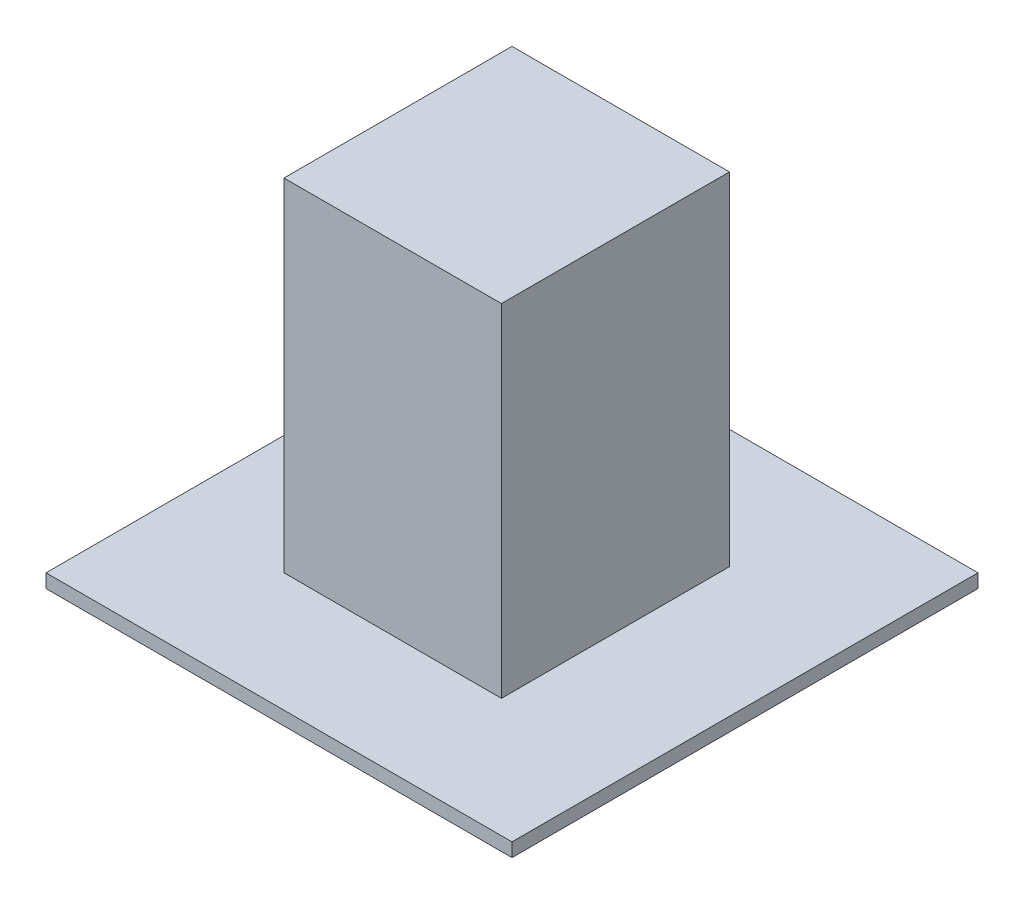
SolidWorks part; units mm, degrees
ref_plane "前视基准面" through (0, 0, 0) normal (0, 0, 1) x (1, 0, 0)
ref_plane "上视基准面" through (0, 0, 0) normal (0, 1, 0) x (1, 0, 0)
ref_plane "右视基准面" through (0, 0, 0) normal (1, 0, 0) x (0, 0, -1)
sketch "草图1" plane through (0, 0, 0) normal (0, 1, 0) x (1, 0, 0)
  line L1 (-68.15, 68.15) -> (68.15, 68.15)
  line L2 (-68.15, 68.15) -> (-68.15, -68.15)
  line L3 (-68.15, -68.15) -> (68.15, -68.15)
  line L4 (68.15, 68.15) -> (68.15, -68.15)
  line L5 (-68.15, 68.15) -> (68.15, -68.15) construction
  line L6 (-68.15, -68.15) -> (68.15, 68.15) construction
  point P0 (0, 0)
  dimension "D1" = 136.3
extrude "凸台-拉伸1" add sketch "草图1" along normal blind 4
sketch "草图2" plane through (0, 4, 0) normal (0, 1, 0) x (1, 0, 0)
  line L0 (30.25, 30.25) -> (-30.25, 30.25)
  line L1 (-30.25, 30.25) -> (-30.25, -30.25)
  line L2 (-30.25, -30.25) -> (30.25, -30.25)
  line L3 (30.25, -30.25) -> (30.25, -33.35)
  line L4 (30.25, -33.35) -> (-33.35, -33.35)
  line L5 (-33.35, -33.35) -> (-33.35, -1.55)
  line L6 (-33.35, 33.35) -> (30.25, 33.35)
  line L7 (30.25, 33.35) -> (30.25, 30.25)
  line L8 (-30.25, 30.25) -> (30.25, -30.25) construction
  line L9 (0, 0) -> (-100.3402, 0) construction
  line L10 (-33.35, 1.55) -> (-63.85, 1.55)
  line L12 (-33.35, -1.55) -> (-63.85, -1.55)
  line L13 (-63.85, 1.55) -> (-63.85, -1.55)
  line L14 (-33.35, 1.55) -> (-33.35, 33.35)
  point P2 (0, 0)
  point P16 (-63.85, 0)
  dimension "D1" = 3.1
  dimension "D2" = 3.1
  dimension "D3" = 3.1
  dimension "D4" = 66.7
  dimension "D5" = 60.5
  dimension "D6" = 63.6
  dimension "D7" = 30.5
  dimension "D8" = 3.1
extrude "凸台-拉伸2" add sketch "草图2" along normal blind 100
sketch "草图3" plane through (0, 0, 1.55) normal (0, 0, 1) x (1, 0, 0)
  line L0 (-63.85, 4) -> (-33.35, 72)
  line L1 (-33.35, 104) -> (-33.35, 4) construction
  line L2 (-33.35, 72) -> (-33.35, 104)
  line L3 (-33.35, 104) -> (-63.85, 104)
  line L4 (-63.85, 104) -> (-63.85, 4)
  line L5 (-63.85, 4) -> (-33.35, 4) construction
  dimension "D1" = 68
extrude "切除-拉伸1" cut sketch "草图3" against normal blind 100
sketch "草图4" plane through (-30.25, 0, 0) normal (1, 0, 0) x (0, 0, -1)
  line L4 (-30.25, 4) -> (30.25, 4)
  line L5 (30.25, 4) -> (30.25, 104)
  line L6 (30.25, 104) -> (-30.25, 104)
  line L7 (-30.25, 104) -> (-30.25, 4)
  line L8 (-30.25, 4) -> (30.25, 4)
  line L9 (30.25, 4) -> (30.25, 104)
  line L10 (30.25, 104) -> (-30.25, 104)
  line L11 (-30.25, 104) -> (-30.25, 4)
  dimension "D1" = 0
extrude "凸台-拉伸3" add sketch "草图4" along normal up to surface (60.5 mm away) up to face at (30.25, 54, -31.8)
